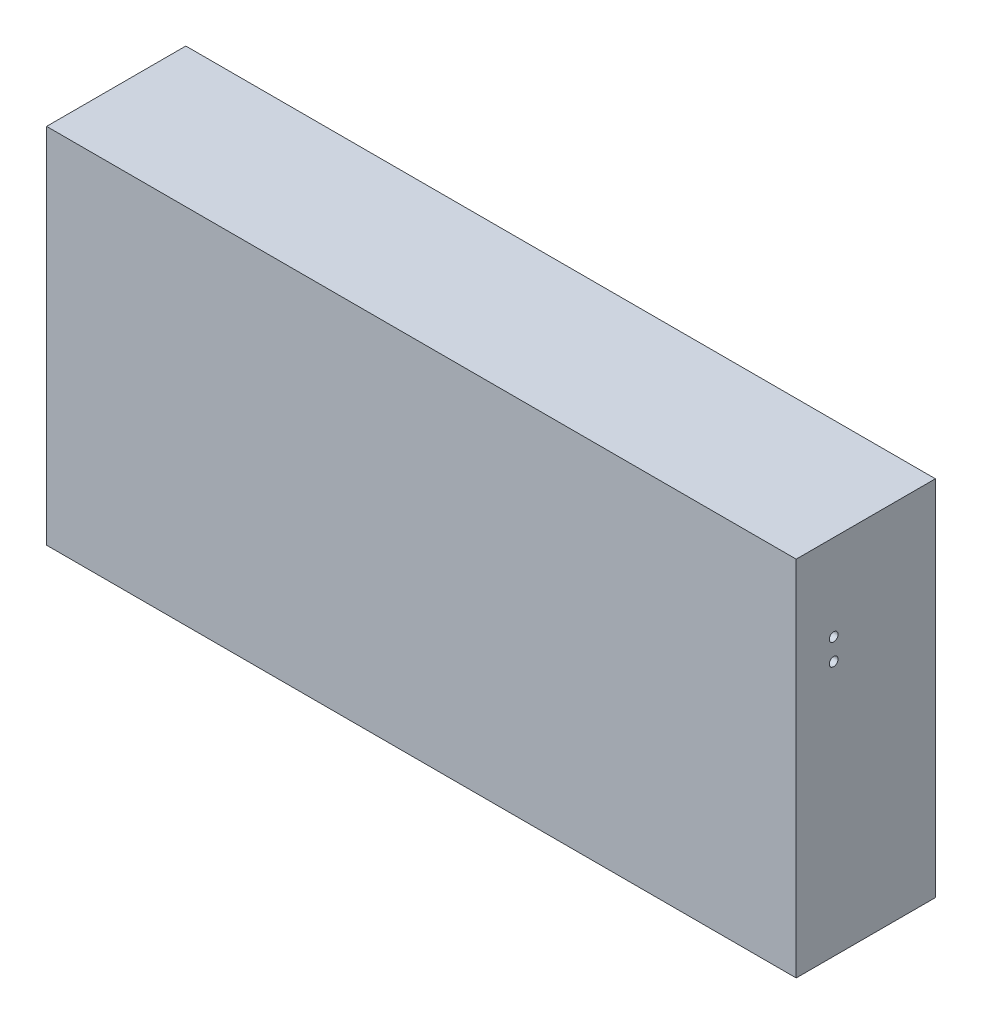
SolidWorks part; units mm, degrees
ref_plane "Front Plane" through (0, 0, 0) normal (0, 0, 1) x (1, 0, 0)
ref_plane "Top Plane" through (0, 0, 0) normal (0, 1, 0) x (1, 0, 0)
ref_plane "Right Plane" through (0, 0, 0) normal (1, 0, 0) x (0, 0, -1)
ref_plane "Plane1" through (0, 135, 0) normal (0, -1, 0) x (1, 0, 0)
sketch "Sketch1" plane through (0, 135, 0) normal (0, -1, 0) x (1, 0, 0)
  line L0 (0, 9) -> (280, 9)
  line L1 (280, 9) -> (280, 61)
  line L2 (280, 61) -> (0, 61)
  line L3 (0, 61) -> (0, 9)
extrude "Tapa frontal" add sketch "Sketch1" against normal blind 3
sketch "Sketch2" plane through (0, 135, 0) normal (0, -1, 0) x (1, 0, 0)
  line L0 (271.25, 9) -> (271.25, 17)
  line L1 (271.25, 17) -> (277, 22.75)
  line L2 (277, 22.75) -> (277, 58)
  line L3 (277, 58) -> (141.5, 58)
  line L4 (141.5, 58) -> (141.5, 24.25)
  line L5 (141.5, 24.25) -> (148.75, 17)
  line L6 (148.75, 17) -> (148.75, 9)
  line L7 (148.75, 9) -> (131.25, 9)
  line L8 (131.25, 9) -> (131.25, 17)
  line L9 (131.25, 17) -> (138.5, 24.25)
  line L10 (138.5, 24.25) -> (138.5, 58)
  line L11 (138.5, 58) -> (3, 58)
  line L12 (3, 58) -> (3, 22.75)
  line L13 (3, 22.75) -> (8.75, 17)
  line L14 (8.75, 17) -> (8.75, 9)
  line L15 (8.75, 9) -> (0, 9)
  line L16 (0, 9) -> (0, 61)
  line L17 (0, 61) -> (280, 61)
  line L18 (280, 61) -> (280, 9)
  line L19 (280, 9) -> (271.25, 9)
extrude "Venas apoyo" add sketch "Sketch2" along normal blind 129
sketch "Sketch3" plane through (0, 6, 0) normal (0, -1, 0) x (1, 0, 0)
  line L0 (280, 61) -> (280, 9)
  line L1 (280, 9) -> (0, 9)
  line L2 (0, 9) -> (0, 61)
  line L3 (0, 61) -> (280, 61)
extrude "Placa unión" add sketch "Sketch3" along normal blind 3.5
sketch "Sketch9" plane through (138.5, 0, 0) normal (-1, 0, 0) x (0, 0, 1)
  line L0 (55, 62) -> (55, 76)
  line L1 (29, 76) -> (29, 62)
  arc A0 (55, 76) -> (29, 76) centre (42, 76) ccw
  arc A1 (29, 62) -> (55, 62) centre (42, 62) ccw
extrude "Cut-Extrude4" cut sketch "Sketch9" against normal up to next
sketch "Sketch10" plane through (0, 6, 0) normal (0, 1, 0) x (-1, 0, 0)
  line L0 (-81, 21) -> (-59, 21)
  line L1 (-59, 43) -> (-81, 43)
  line L3 (-280, 61) -> (0, 61) construction
  line L4 (-199, 43) -> (-221, 43)
  line L5 (-221, 21) -> (-199, 21)
  arc A0 (-81, 43) -> (-81, 21) centre (-81, 32) ccw
  arc A1 (-59, 21) -> (-59, 43) centre (-59, 32) ccw
  arc A2 (-199, 21) -> (-199, 43) centre (-199, 32) ccw
  arc A3 (-221, 43) -> (-221, 21) centre (-221, 32) ccw
  dimension "D2" = 11
  dimension "D1" = 22
  dimension "D3" = 18
  dimension "D4" = 2
extrude "Cut-Extrude5" cut sketch "Sketch10" against normal through all
hole_wizard "Ø4.3 (4.3) Diameter Hole1" positions "Sketch13" profile "Sketch12" hole size "Ø4.3" standard "ANSI Metric"
sketch "Sketch13" plane through (0, 6, 0) normal (0, 1, 0) x (1, 0, 0)
  point P0 (245, -46)
  point P1 (175, -46)
  point P2 (245, -20)
  point P3 (175, -20)
  point P4 (105, -46)
  point P5 (35, -46)
  point P6 (105, -20)
  point P7 (35, -20)
sketch "Sketch12" plane through (245, 6, 46) normal (1, 0, 0) x (0, 0, 1)
  line L0 (0, 0) -> (0, 3.5)
  line L1 (0, 3.5) -> (2.15, 3.5)
  line L2 (2.15, 3.5) -> (2.15, 0)
  line L5 (2.15, 0) -> (0, 0)
  line L11 (0, -6.35) -> (0, 107.95) construction
  dimension "Thru Hole Dia." = 4.3
  dimension "Thru Hole Depth" = 3.5
hole_wizard "Ø2.5 (3) Diameter Hole1" positions "Sketch15" profile "Sketch14" hole size "Ø2.5" standard "ANSI Metric"
sketch "Sketch15" plane through (0, 0, 9) normal (0, 0, -1) x (-1, 0, 0)
  point P0 (-275.5, 126)
  point P1 (-144.5, 126)
  point P2 (-275.5, 104)
  point P3 (-275.5, 82)
  point P4 (-144.5, 104)
  point P5 (-144.5, 82)
  point P6 (-135.5, 126)
  point P7 (-4.5, 126)
  point P8 (-135.5, 104)
  point P9 (-135.5, 82)
  point P10 (-4.5, 104)
  point P11 (-4.5, 82)
  point P12 (-275.5, 60)
  point P13 (-144.5, 60)
  point P14 (-275.5, 38)
  point P15 (-275.5, 16)
  point P16 (-144.5, 38)
  point P17 (-144.5, 16)
  point P18 (-135.5, 60)
  point P19 (-4.5, 60)
  point P20 (-135.5, 38)
  point P21 (-135.5, 16)
  point P22 (-4.5, 38)
  point P23 (-4.5, 16)
sketch "Sketch14" plane through (275.5, 126, 9) normal (1, 0, 0) x (0, 1, 0)
  line L0 (0, 0) -> (0, 10)
  line L1 (0, 10) -> (1.5, 10)
  line L2 (1.5, 10) -> (1.5, 0)
  line L5 (1.5, 0) -> (0, 0)
  line L10 (0, 10) -> (-1.5, 10) construction
  line L11 (0, -6.35) -> (0, 107.95) construction
  dimension "Hole Dia." = 3
  dimension "Hole Depth" = 10
  dimension "Drill Angle" = 180
sketch "Sketch16" plane through (0, 0, 61) normal (0, 0, 1) x (1, 0, 0)
  line L5 (280, 138) -> (280, 2.5) construction
  line L6 (280, 104) -> (295, 104)
  line L7 (280, 104) -> (280, 86)
  line L8 (280, 86) -> (295, 86)
  line L9 (298, 101) -> (298, 89)
  line L10 (140, 138) -> (140, 3.7181) construction
  line L11 (280, 138) -> (0, 138) construction
  line L12 (280, 138) -> (0, 138) construction
  line L13 (-18, 101) -> (-18, 89)
  line L14 (0, 86) -> (-15, 86)
  line L15 (0, 104) -> (0, 86)
  line L16 (0, 104) -> (-15, 104)
  circle A0 centre (290.3818, 95) radius 3.15
  circle A1 centre (-10.3818, 95) radius 3.15
  arc A2 (295, 86) -> (298, 89) centre (295, 89) ccw
  arc A3 (295, 104) -> (298, 101) centre (295, 101) cw
  arc A4 (-18, 89) -> (-15, 86) centre (-15, 89) ccw
  arc A5 (-18, 101) -> (-15, 104) centre (-15, 101) cw
  point P22 (298, 95)
  point P27 (298, 86)
  point P30 (298, 104)
  point P33 (-18, 86)
  point P36 (-18, 104)
  dimension "D3" = 6.3
  dimension "D5" = 3
  dimension "D6" = 3
  dimension "D1" = 18
  dimension "D2" = 18
  dimension "D4" = 34
extrude "Anclajes" [suppressed] add sketch "Sketch16" against normal blind 4
sketch "Sketch17" plane through (0, 0, 58) normal (0, 0, -1) x (-1, 0, 0)
  circle A0 centre (-238.9223, 87.46) radius 3
  circle A1 centre (-238.9223, 87.46) radius 1.5
  circle A2 centre (-238.9223, 51.154) radius 3
  circle A3 centre (-238.9223, 51.154) radius 1.5
  circle A4 centre (-184.6933, 51.154) radius 3
  circle A5 centre (-184.6933, 51.154) radius 1.5
  circle A6 centre (-184.6933, 87.46) radius 3
  circle A7 centre (-184.6933, 87.46) radius 1.5
  circle A8 centre (-96.5374, 87.46) radius 3
  circle A9 centre (-96.5374, 87.46) radius 1.5
  circle A10 centre (-42.3084, 87.46) radius 3
  circle A11 centre (-42.3084, 87.46) radius 1.5
  circle A12 centre (-42.3084, 51.154) radius 3
  circle A13 centre (-42.3084, 51.154) radius 1.5
  circle A14 centre (-96.5374, 51.154) radius 3
  circle A15 centre (-96.5374, 51.154) radius 1.5
  dimension "D1" = 6
  dimension "D2" = 3
extrude "Boss-Extrude1" add sketch "Sketch17" along normal blind 5
fillet "Fillet1" radius 3 8 edges at (45.3084, 51.154, 58) (45.3084, 87.46, 58) (99.5374, 51.154, 58) (99.5374, 87.46, 58) (241.9223, 87.46, 58) (187.6933, 87.46, 58) (187.6933, 51.154, 58) (241.9223, 51.154, 58)
fillet "Fillet2" [suppressed] radius 5
sketch "Sketch18" plane through (0, 0, 0) normal (-1, 0, 0) x (0, 0, 1)
  circle A0 centre (47, 105.8568) radius 1.65
  circle A1 centre (47, 97.8568) radius 1.65
  dimension "D1" = 3.3
extrude "Cut-Extrude6" cut sketch "Sketch18" against normal through all
